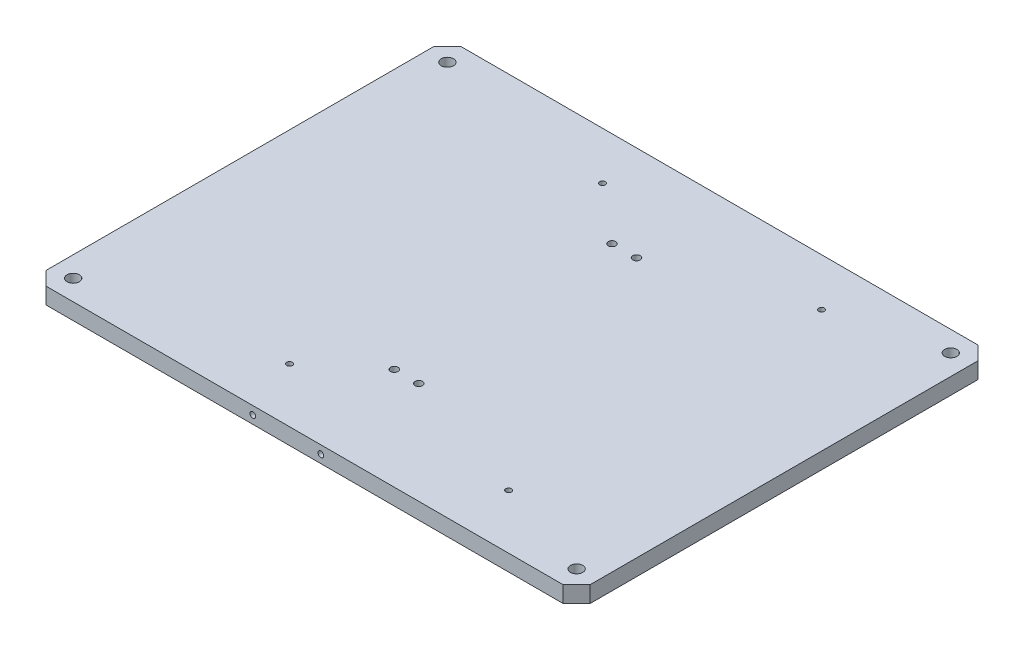
SolidWorks part; units mm, degrees
ref_plane "Front" through (0, 0, 0) normal (0, 0, 1) x (1, 0, 0)
ref_plane "Top" through (0, 0, 0) normal (0, 1, 0) x (1, 0, 0)
ref_plane "Right" through (0, 0, 0) normal (1, 0, 0) x (0, 0, -1)
sketch "Sketch1" plane through (0, 0, 0) normal (0, 1, 0) x (1, 0, 0)
  line L0 (-107.6983, 0) -> (113.7121, 0) construction
  line L1 (0, 37.0036) -> (0, -148.9284) construction
  line L3 (-200, 0) -> (200, 0)
  line L4 (-200, 0) -> (-200, -305)
  line L5 (-200, -305) -> (200, -305)
  line L6 (200, 0) -> (200, -305)
  dimension "D1" = 400
  dimension "D2" = 305
extrude "Boss-Extrude1" add sketch "Sketch1" along normal blind 12
hole_wizard "CBORE for M5 Socket Head Cap Screw1" positions "Sketch2" profile "Sketch3" counterbore size "M5" standard "JIS" end condition through all
sketch "Sketch2" plane through (0, 0, 0) normal (0, -1, 0) x (1, 0, 0)
  line L0 (0, 112.102) -> (0, -48.5148) construction
  line L3 (-38.9175, 0) -> (69.9004, 0) construction
  line L5 (-200, 305) -> (200, 305) construction
  point P0 (-9, 230)
  point P1 (-9, 70)
  point P3 (9, 70)
  point P5 (9, 230)
  dimension "D1" = 70
  dimension "D2" = 18
  dimension "D3" = 160
  dimension "D4" = 75
sketch "Sketch3" plane through (-9, 0, 230) normal (1, 0, 0) x (0, 0, -1)
  line L0 (0, 0) -> (0, 12)
  line L1 (0, 12) -> (2.75, 12)
  line L3 (2.75, 12) -> (2.75, 5)
  line L4 (2.75, 5) -> (5, 5)
  line L5 (5, 5) -> (5, 0)
  line L7 (5, 0) -> (0, 0)
  line L11 (0, -6.35) -> (0, 107.95) construction
  dimension "通し穴の直径" = 5.5
  dimension "通し穴の深さ" = 12
  dimension "座ぐり穴の直径" = 10
  dimension "座ぐり穴の深さ" = 5
hole_wizard "M5x0.8 Tapped Hole1" positions "Sketch4" profile "Sketch5" tap size "M5x0.8" standard "JIS"
sketch "Sketch4" plane through (0, 0, 305) normal (0, 0, 1) x (1, 0, 0)
  line L0 (0, 22.9424) -> (0, -21.9523) construction
  line L2 (-200, 0) -> (200, 0) construction
  point P0 (-38, 6)
  point P1 (12, 6)
  dimension "D1" = 6
  dimension "D2" = 50
  dimension "D3" = 12
sketch "Sketch5" plane through (-38, 6, 305) normal (1, 0, 0) x (0, -1, 0)
  line L0 (0, 0) -> (0, 15.2618)
  line L1 (0, 15.2618) -> (2.1, 14)
  line L2 (2.1, 14) -> (2.1, 0)
  line L5 (2.1, 0) -> (0, 0)
  line L10 (0, 15.2618) -> (-2.1, 14) construction
  line L11 (0, -6.35) -> (0, 107.95) construction
  dimension "ねじ下穴ﾄﾞﾘﾙ直径" = 4.2
  dimension "ねじ下穴ﾄﾞﾘﾙの深さ" = 14
  dimension "ﾄﾞﾘﾙ角度" = 118
cosmetic thread "Hole Thread1" parameters "D1"=10, "D2"=5
cosmetic thread "Hole Thread2" parameters "D1"=10, "D2"=5
chamfer "Chamfer1" distance 10 angle 45 4 edges at (200, 6, 305) (-200, 6, 305) (200, 6, 0) (-200, 6, 0)
hole_wizard "M8 Clearance Hole1" positions "Sketch6" profile "Sketch7" hole size "M8" standard "JIS" end condition through all
sketch "Sketch6" plane through (0, 12, 0) normal (0, 1, 0) x (-1, 0, 0)
  line L0 (0, -21.6549) -> (0, 317.4235) construction
  line L2 (-222.0875, 152.5) -> (224.9279, 152.5) construction
  point P0 (185, 290)
  point P1 (185, 15)
  point P3 (-185, 15)
  point P5 (-185, 290)
  dimension "D1" = 152.5
  dimension "D2" = 370
  dimension "D3" = 275
sketch "Sketch7" plane through (-185, 12, 290) normal (1, 0, 0) x (0, 0, 1)
  line L0 (0, 0) -> (0, 12)
  line L1 (0, 12) -> (4.5, 12)
  line L2 (4.5, 12) -> (4.5, 0)
  line L5 (4.5, 0) -> (0, 0)
  line L11 (0, -6.35) -> (0, 107.95) construction
  dimension "通し穴の直径" = 9
  dimension "通し穴の深さ" = 12
hole_wizard "M5x0.8 Tapped Hole2" positions "Sketch8" profile "Sketch9" tap size "M5x0.8" standard "JIS" end condition through all
sketch "Sketch8" plane through (0, 12, 0) normal (0, 1, 0) x (-1, 0, 0)
  line L0 (-224.2178, 150) -> (213.9212, 150) construction
  line L2 (200, 10) -> (200, 295) construction
  point P0 (51, 265)
  point P1 (51, 35)
  point P13 (-110, 265)
  point P15 (-110, 35)
  dimension "D1" = 150
  dimension "D2" = 230
  dimension "D3" = 149
  dimension "D4" = 161
sketch "Sketch9" plane through (-51, 12, 265) normal (1, 0, 0) x (0, 0, 1)
  line L0 (0, 0) -> (0, 12)
  line L1 (0, 12) -> (2.1, 12)
  line L2 (2.1, 12) -> (2.1, 0)
  line L5 (2.1, 0) -> (0, 0)
  line L11 (0, -6.35) -> (0, 107.95) construction
  dimension "次ｻｰﾌｪｽまでのねじ下穴ﾄﾞﾘﾙ直径" = 4.2
  dimension "次ｻｰﾌｪｽまでのねじ下穴ﾄﾞﾘﾙの深さ" = 12
cosmetic thread "Hole Thread3" parameters "D2"=5
cosmetic thread "Hole Thread4" parameters "D2"=5
cosmetic thread "Hole Thread5" parameters "D2"=5
cosmetic thread "Hole Thread6" parameters "D2"=5
